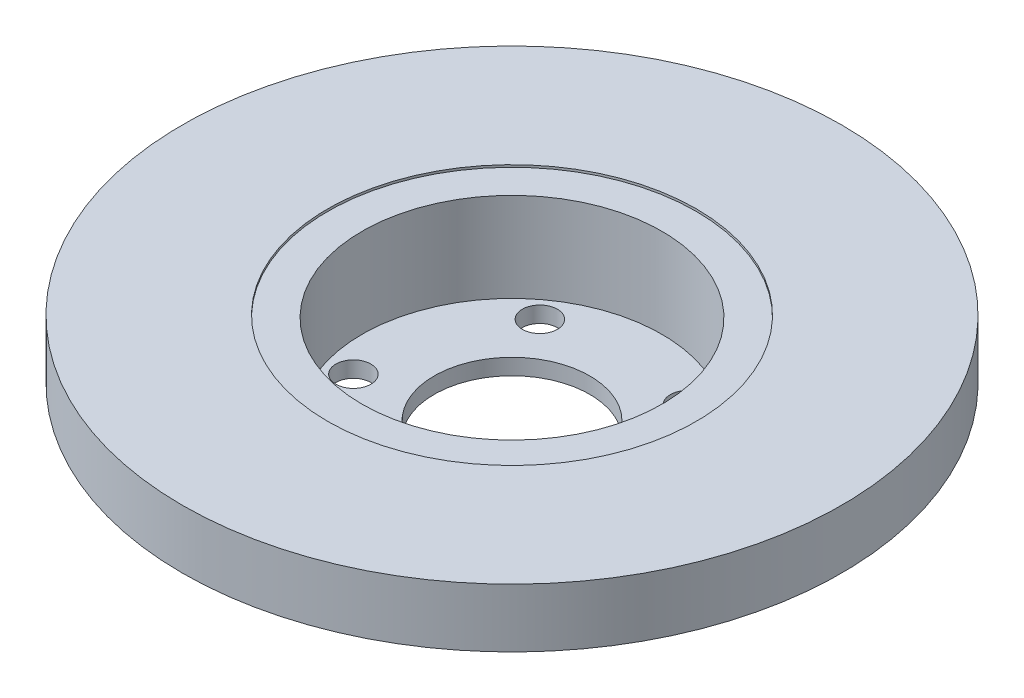
SolidWorks part; units mm, degrees
ref_plane "Front Plane" through (0, 0, 0) normal (0, 0, 1) x (1, 0, 0)
ref_plane "Top Plane" through (0, 0, 0) normal (0, 1, 0) x (1, 0, 0)
ref_plane "Right Plane" through (0, 0, 0) normal (1, 0, 0) x (0, 0, -1)
sketch "Sketch1" plane through (0, 0, 0) normal (0, 1, 0) x (1, 0, 0)
  line L1 (0, 0) -> (290, 0)
  line L2 (0, 0) -> (0, -290)
  line L3 (0, -290) -> (290, -290)
  line L4 (290, 0) -> (290, -290)
  dimension "D1" = 290
  dimension "D2" = 290
extrude "Boss-Extrude1" add sketch "Sketch1" along normal blind 47
sketch "Sketch2" plane through (0, 47, 0) normal (0, 1, 0) x (1, 0, 0)
  line L0 (0, 0) -> (290, -290) construction
  circle A0 centre (145, -145) radius 65.5
  dimension "D1" = 131
extrude "Cut-Extrude1" cut sketch "Sketch2" against normal blind 40
sketch "Sketch3" plane through (0, 47, 0) normal (0, 1, 0) x (1, 0, 0)
  circle A0 centre (145, -145) radius 80.5
  dimension "D1" = 161
extrude "Cut-Extrude2" cut sketch "Sketch3" against normal blind 1
sketch "Sketch4" plane through (0, 0, 0) normal (0, -1, 0) x (1, 0, 0)
  line L0 (0, 290) -> (290, 0) construction
  circle A0 centre (145, 145) radius 74.125
  dimension "D1" = 148.25
extrude "Cut-Extrude3" cut sketch "Sketch4" against normal blind 21.33 flip side to cut
sketch "Sketch5" plane through (0, 0, 0) normal (0, -1, 0) x (1, 0, 0)
  circle A0 centre (145, 145) radius 34
  dimension "D1" = 68
extrude "Cut-Extrude4" cut sketch "Sketch5" against normal through all both and the other way through all
sketch "Sketch6" plane through (0, 0, 0) normal (0, -1, 0) x (1, 0, 0)
  line L0 (145, 145) -> (145, 290) construction
  line L1 (290, 290) -> (0, 290) construction
  circle A0 centre (145, 200) radius 7.65
  circle A1 centre (197.3081, 161.9959) radius 7.65
  circle A2 centre (177.3282, 100.5041) radius 7.65
  circle A3 centre (112.6718, 100.5041) radius 7.65
  circle A4 centre (92.6919, 161.9959) radius 7.65
  point P18 (145, 145)
  dimension "D1" = 15.3
  dimension "D2" = 55
  dimension "D3" = 5
extrude "Cut-Extrude5" cut sketch "Sketch6" against normal through all both and the other way through all
sketch "Sketch7" plane through (0, 21.33, 0) normal (0, -1, 0) x (1, 0, 0)
  circle A0 centre (145, 145) radius 74.125
  circle A1 centre (145, 145) radius 80.5
  dimension "D1" = 161
extrude "Cut-Extrude6" cut sketch "Sketch7" against normal blind 15
sketch "Sketch8" plane through (0, 21.33, 0) normal (0, -1, 0) x (1, 0, 0)
  line L0 (145, 145) -> (145, 290) construction
  line L1 (290, 290) -> (0, 290) construction
  line L2 (254.9216, 230.1014) -> (211.9208, 195.8095)
  line L3 (143, 284) -> (147, 284)
  line L4 (143, 284) -> (143, 229)
  line L5 (143, 229) -> (147, 229)
  line L6 (147, 284) -> (147, 229)
  line L7 (252.4276, 233.2287) -> (209.4269, 198.9368)
  line L8 (209.4269, 198.9368) -> (211.9208, 195.8095)
  line L9 (252.4276, 233.2287) -> (254.9216, 230.1014)
  line L10 (280.0699, 112.1197) -> (226.4489, 124.3584)
  line L11 (280.96, 116.0194) -> (227.339, 128.2581)
  line L12 (227.339, 128.2581) -> (226.4489, 124.3584)
  line L13 (280.96, 116.0194) -> (280.0699, 112.1197)
  line L14 (203.5079, 18.8976) -> (179.6443, 68.4508)
  line L15 (207.1118, 20.6331) -> (183.2482, 70.1864)
  line L16 (183.2482, 70.1864) -> (179.6443, 68.4508)
  line L17 (207.1118, 20.6331) -> (203.5079, 18.8976)
  line L18 (82.8882, 20.6331) -> (106.7518, 70.1864)
  line L19 (86.4921, 18.8976) -> (110.3557, 68.4508)
  line L20 (110.3557, 68.4508) -> (106.7518, 70.1864)
  line L21 (86.4921, 18.8976) -> (82.8882, 20.6331)
  line L22 (9.04, 116.0194) -> (62.661, 128.2581)
  line L23 (9.9301, 112.1197) -> (63.5511, 124.3584)
  line L24 (63.5511, 124.3584) -> (62.661, 128.2581)
  line L25 (9.9301, 112.1197) -> (9.04, 116.0194)
  line L26 (37.5724, 233.2287) -> (80.5731, 198.9368)
  line L27 (35.0784, 230.1014) -> (78.0792, 195.8095)
  line L28 (78.0792, 195.8095) -> (80.5731, 198.9368)
  line L29 (35.0784, 230.1014) -> (37.5724, 233.2287)
  point P9 (145, 229)
  point P37 (145, 145)
  dimension "D1" = 4
  dimension "D2" = 55
  dimension "D3" = 84
  dimension "D4" = 7
extrude "Cut-Extrude7" cut sketch "Sketch8" against normal blind 2
sketch "Sketch9" plane through (0, 21.33, 0) normal (0, -1, 0) x (1, 0, 0)
  circle A0 centre (145, 145) radius 144
  dimension "D1" = 288
extrude "Cut-Extrude8" cut sketch "Sketch9" against normal through all both and the other way through all flip side to cut
